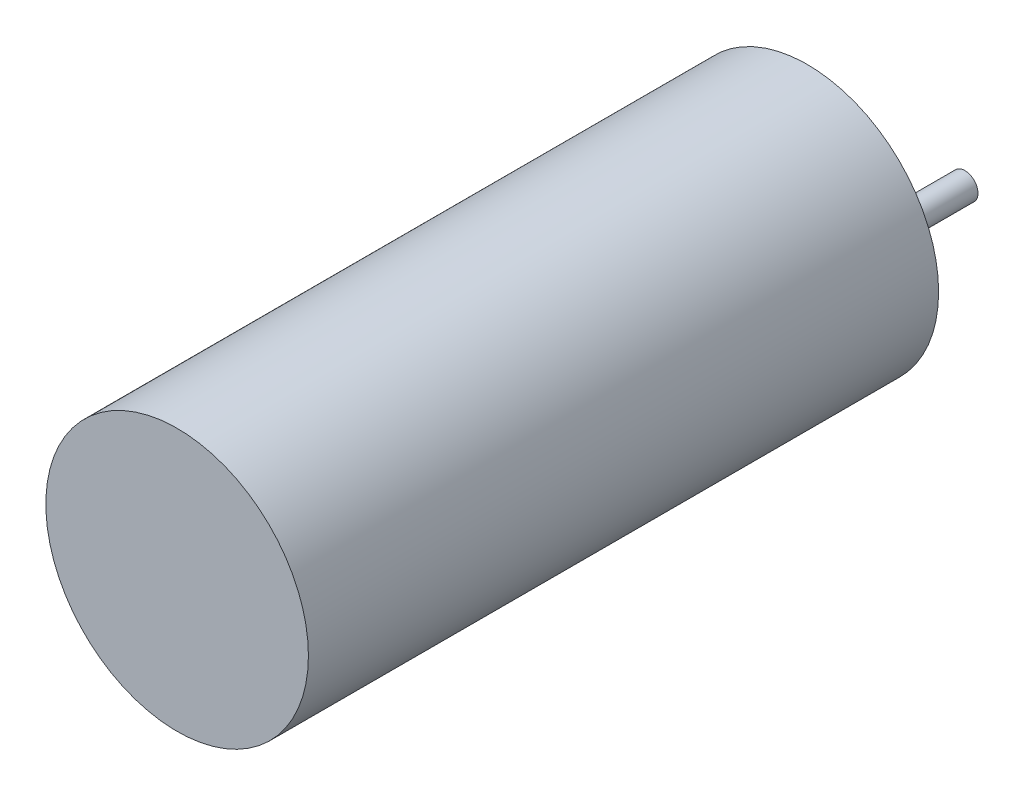
SolidWorks part; units mm, degrees
ref_plane "Front Plane" through (0, 0, 0) normal (0, 0, 1) x (1, 0, 0)
ref_plane "Top Plane" through (0, 0, 0) normal (0, 1, 0) x (1, 0, 0)
ref_plane "Right Plane" through (0, 0, 0) normal (1, 0, 0) x (0, 0, -1)
sketch "Sketch1" plane through (0, 0, 0) normal (0, 0, 1) x (1, 0, 0)
  circle A0 centre (0, 0) radius 2.5
  dimension "D1" = 5
extrude "Boss-Extrude1" add sketch "Sketch1" along normal blind 12
ref_plane "Plane1" through (1, 0, 0) normal (1, 0, 0) x (0, 0, -1)
sketch "Sketch2" plane through (1, 0, 0) normal (1, 0, 0) x (0, 0, -1)
  line L0 (0, 0) -> (2, 0)
  dimension "D1" = 2
sketch "Sketch3" plane through (0, 0, 0) normal (0, 0, -1) x (-1, 0, 0)
  circle A0 centre (-1, 0) radius 0.25
  dimension "D1" = 0.5
sweep "Sweep1" add profiles "Sketch3" path "Sketch2"
mirror "Mirror1" about plane through (0, 0, 0) normal (1, 0, 0) of "Sweep1"
